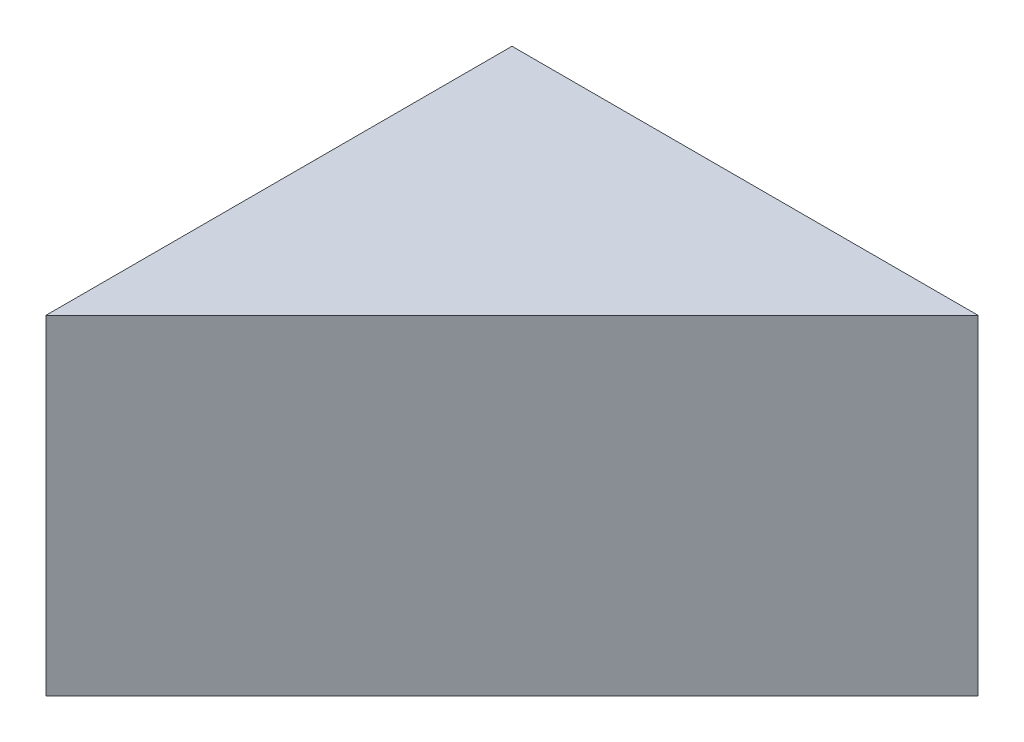
SolidWorks part; units mm, degrees
ref_plane "Front" through (0, 0, 0) normal (0, 0, 1) x (1, 0, 0)
ref_plane "Top" through (0, 0, 0) normal (0, 1, 0) x (1, 0, 0)
ref_plane "Right" through (0, 0, 0) normal (1, 0, 0) x (0, 0, -1)
sketch "Sketch1" plane through (0, 0, 0) normal (0, 1, 0) x (1, 0, 0)
  line L0 (0, 0) -> (0, -14.1421)
  line L1 (0, -14.1421) -> (14.1421, 0)
  line L2 (14.1421, 0) -> (0, 0)
  dimension "D1" = 10
  dimension "D2" = 45
extrude "Boss-Extrude1" add sketch "Sketch1" along normal mid plane 10
